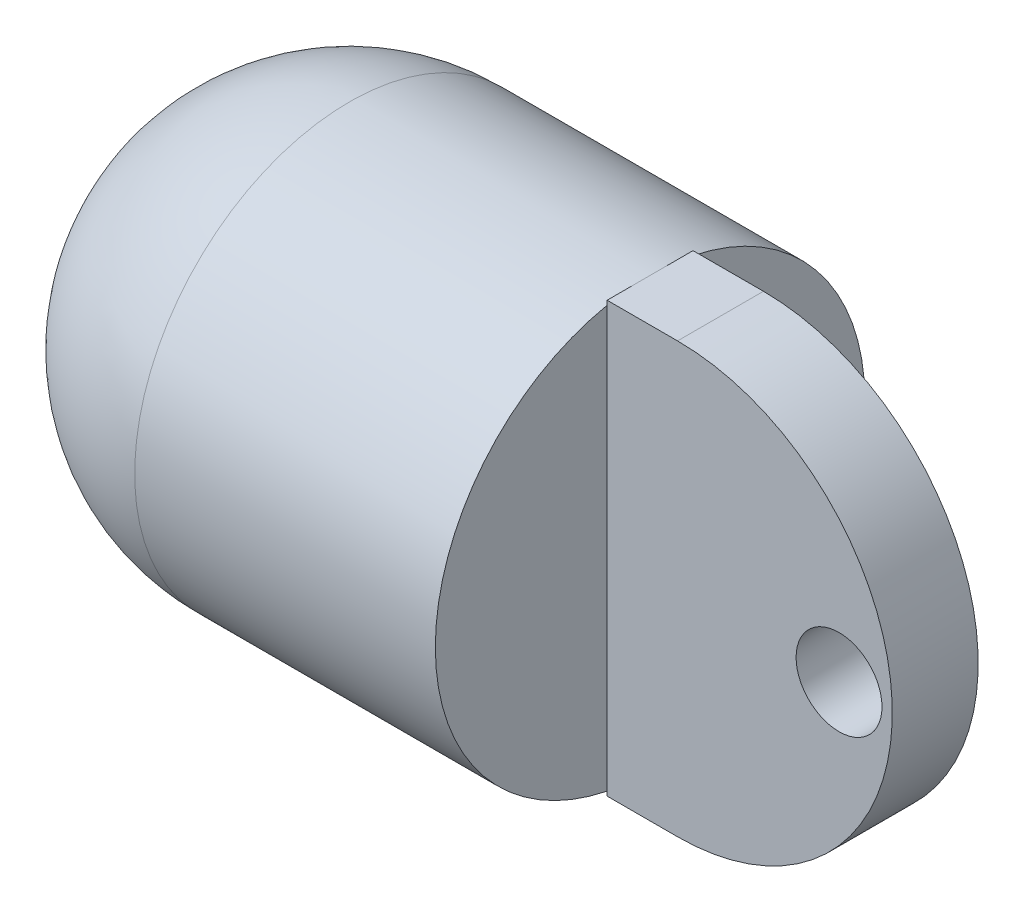
SolidWorks part; units mm, degrees
ref_plane "Front Plane" through (0, 0, 0) normal (0, 0, 1) x (1, 0, 0)
ref_plane "Top Plane" through (0, 0, 0) normal (0, 1, 0) x (1, 0, 0)
ref_plane "Right Plane" through (0, 0, 0) normal (1, 0, 0) x (0, 0, -1)
sketch "Sketch1" plane through (0, 0, 0) normal (1, 0, 0) x (0, 0, -1)
  circle A0 centre (0, 0) radius 12.5
  dimension "D1" = 25
extrude "Boss-Extrude1" add sketch "Sketch1" against normal blind 17.5
sketch "Sketch6" plane through (0, 0, 0) normal (1, 0, 0) x (0, 0, -1)
  line L0 (-2.5, 12.5) -> (-2.5, -12.5)
  line L1 (-2.5, 12.5) -> (2.5, 12.5)
  line L2 (-2.5, -12.5) -> (2.5, -12.5)
  line L3 (2.5, 12.5) -> (2.5, -12.5)
  line L4 (-2.5, 12.5) -> (2.5, -12.5) construction
  line L5 (-2.5, -12.5) -> (2.5, 12.5) construction
  point P1 (0, 0)
  dimension "D1" = 5
  dimension "D2" = 25
extrude "Boss-Extrude3" add sketch "Sketch6" along normal blind 4.1
sketch "Sketch8" plane through (0, 0, 2.5) normal (0, 0, 1) x (1, 0, 0)
  line L0 (4.1, 12.5) -> (4.1, -12.5) construction
  line L1 (4.1, 12.5) -> (4.1, -12.5)
  arc A0 (4.1, -12.5) -> (4.1, 12.5) centre (4.1, 0) ccw
extrude "Boss-Extrude4" add sketch "Sketch8" against normal blind 5
sketch "Sketch10" plane through (0, 0, 2.5) normal (0, 0, 1) x (1, 0, 0)
  line L0 (0, 12.2474) -> (0, -12.2474) construction
  line L1 (4.1, -12.5) -> (0, -12.5) construction
  circle A0 centre (13.5, 0) radius 2.5
  dimension "D1" = 5
  dimension "D2" = 13.5
  dimension "D3" = 12.5
extrude "Cut-Extrude1" cut sketch "Sketch10" against normal through all and the other way through all
sketch "Sketch11" plane through (-17.5, 0, 0) normal (-1, 0, 0) x (0, 0, 1)
  line L0 (0, 12.5) -> (0, -12.5)
  arc A0 (0, -12.5) -> (0, 12.5) centre (0, 0) ccw
revolve "Revolve1" add sketch "Sketch11" angle 180 about L0
